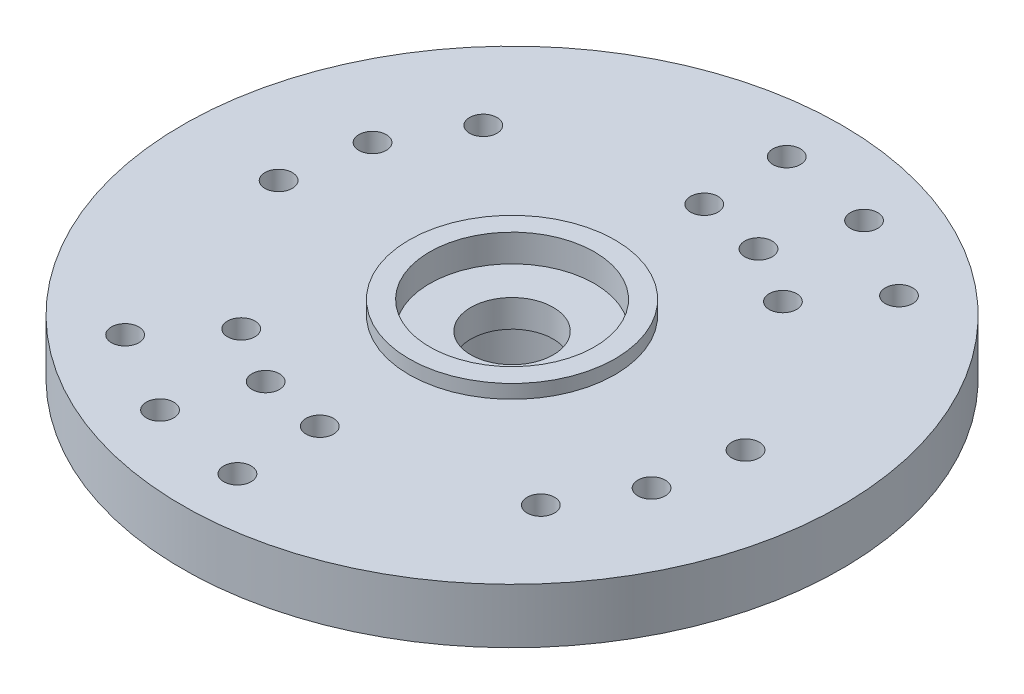
SolidWorks part; units mm, degrees
material "PVC rigide"
ref_plane "Plan de face" through (0, 0, 0) normal (0, 0, 1) x (1, 0, 0)
ref_plane "Plan de dessus" through (0, 0, 0) normal (0, 1, 0) x (1, 0, 0)
ref_plane "Plan de droite" through (0, 0, 0) normal (1, 0, 0) x (0, 0, -1)
sketch "Esquisse1" plane through (0, 0, 0) normal (0, 0, 1) x (1, 0, 0)
  line L0 (0, 0) -> (0, 5) construction
  line L1 (2.75, 0) -> (2.75, 3)
  line L2 (2.75, 3) -> (1.5, 3)
  line L3 (1.5, 3) -> (1.5, 4)
  line L4 (1.5, 4) -> (3, 4)
  line L5 (3, 4) -> (3, 5)
  line L6 (3, 5) -> (3.75, 5)
  line L7 (3.75, 5) -> (3.75, 4.5)
  line L8 (3.75, 4.5) -> (12, 4.5)
  line L9 (12, 4.5) -> (12, 2.5)
  line L10 (12, 2.5) -> (4.5, 2.5)
  line L11 (4.5, 2.5) -> (4.5, 0)
  line L12 (4.5, 0) -> (2.75, 0)
  dimension "D1" = 6
  dimension "D2" = 7.5
  dimension "D3" = 3
  dimension "D4" = 5.5
  dimension "D5" = 9
  dimension "D6" = 24
  dimension "D7" = 0.5
  dimension "D8" = 2
  dimension "D9" = 2.5
  dimension "D10" = 3
  dimension "D11" = 1
revolve "Révolution1" add sketch "Esquisse1" angle 360 about L0
sketch "Esquisse2" plane through (0, 4.5, 0) normal (0, 1, 0) x (1, 0, 0)
  line L0 (0, 10) -> (0, 0) construction
  line L1 (0, 0) -> (8.5, 0) construction
  circle A0 centre (0, 10) radius 0.5
  circle A1 centre (8.5, 0) radius 0.5
  circle A2 centre (0, 7) radius 0.5
  circle A3 centre (0, -7) radius 0.5
  circle A4 centre (0, -10) radius 0.5
  circle A5 centre (-8.5, 0) radius 0.5
  dimension "D1" = 1
  dimension "D2" = 20
  dimension "D3" = 14
  dimension "D4" = 17
extrude "Enlèv. mat.-Extru.1" cut sketch "Esquisse2" against normal blind 10
pattern_circular "Répétition circulaire1" count 3 every 20 about axis through (0, 0, 0) along (0, 1, 0) of "Enlèv. mat.-Extru.1"
